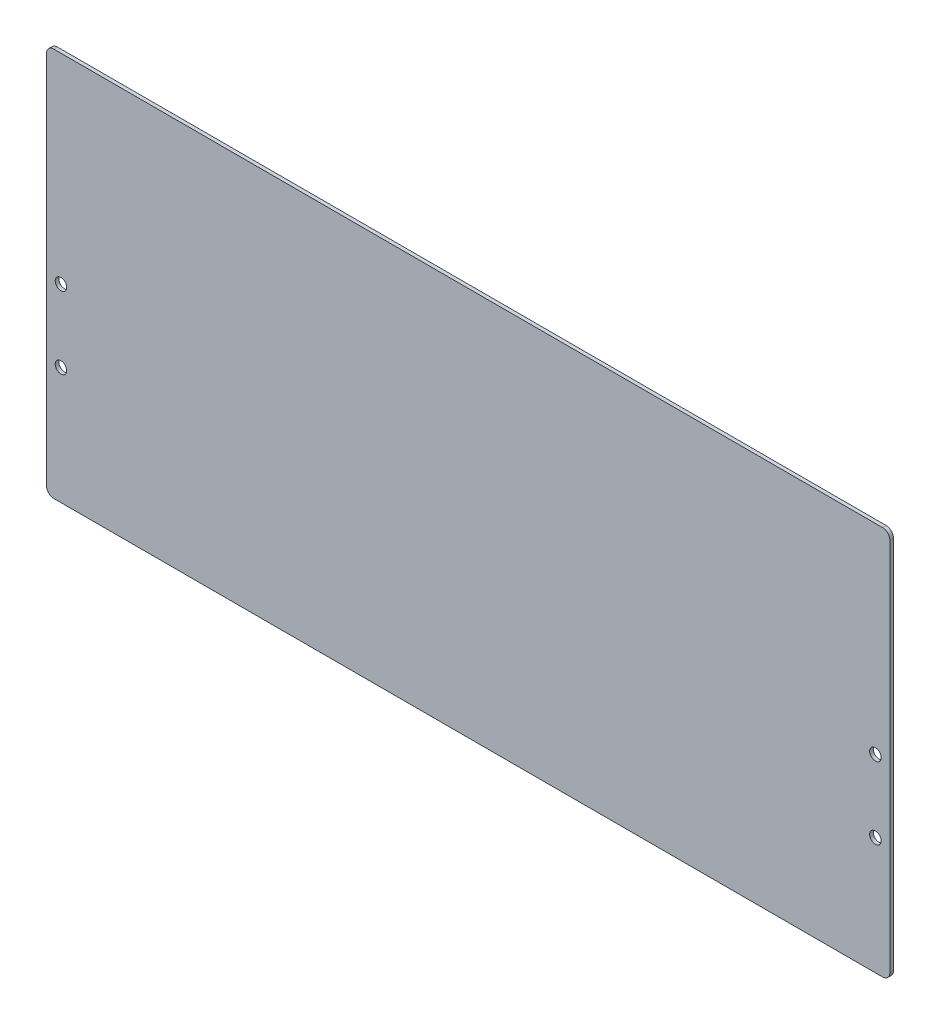
SolidWorks part; units mm, degrees
material "Thornel Mat VMA"
ref_plane "前视基准面" through (0, 0, 0) normal (0, 0, 1) x (1, 0, 0)
ref_plane "上视基准面" through (0, 0, 0) normal (0, 1, 0) x (1, 0, 0)
ref_plane "右视基准面" through (0, 0, 0) normal (1, 0, 0) x (0, 0, -1)
other "Configuration Table"
sketch "草图1" plane through (0, 0, 0) normal (0, 0, 1) x (1, 0, 0)
  line L0 (-113, 54) -> (-113, -54) construction
  line L1 (-117, -54) -> (117, -54)
  line L2 (-117, -54) -> (-117, 54)
  line L3 (-117, 54) -> (117, 54)
  line L4 (117, -54) -> (117, 54)
  line L5 (-117, -54) -> (117, 54) construction
  line L6 (-117, 54) -> (117, -54) construction
  line L7 (0, 0) -> (0, -50000) construction
  circle A0 centre (-113, -1.5) radius 1.6
  circle A1 centre (-113, -21.5) radius 1.6
  circle A2 centre (113, -21.5) radius 1.6
  circle A3 centre (113, -1.5) radius 1.6
  point P0 (0, 0)
  dimension "D3" = 20
  dimension "D4" = 3.2
  dimension "D6" = 32.5
  dimension "D1" = 234
  dimension "D2" = 108
  dimension "D5" = 4
extrude "凸台-拉伸1" add sketch "草图1" along normal blind 1
fillet "圆角1" radius 2 4 edges at (117, -54, 0.5) (-117, -54, 0.5) (-117, 54, 0.5) (117, 54, 0.5)
